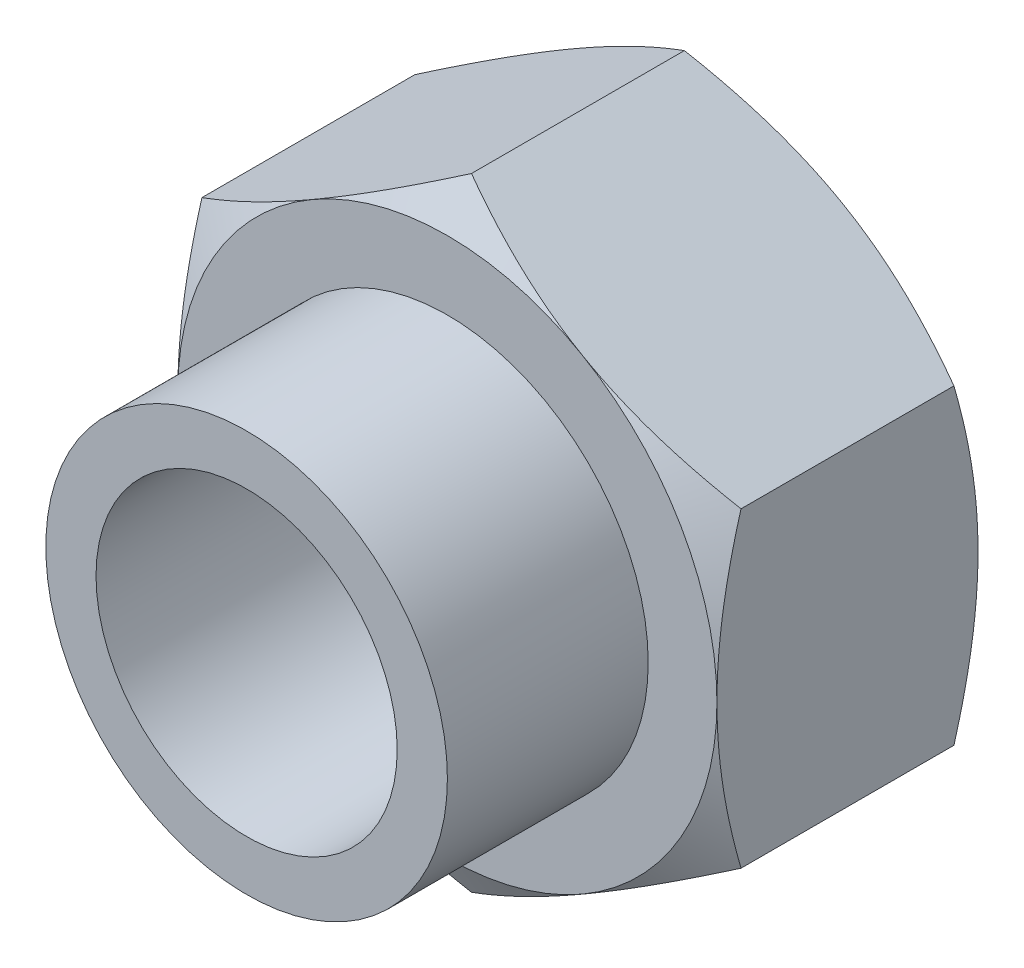
SolidWorks part; units mm, degrees
ref_plane "Front Plane" through (0, 0, 0) normal (0, 0, 1) x (1, 0, 0)
ref_plane "Top Plane" through (0, 0, 0) normal (0, 1, 0) x (1, 0, 0)
ref_plane "Right Plane" through (0, 0, 0) normal (1, 0, 0) x (0, 0, -1)
sketch "Sketch1" plane through (0, 0, 0) normal (0, 0, 1) x (1, 0, 0)
  line L1 (0, 77.5) -> (-67.117, 38.75)
  line L2 (-67.117, 38.75) -> (-67.117, -38.75)
  line L3 (-67.117, -38.75) -> (0, -77.5)
  line L4 (0, -77.5) -> (67.117, -38.75)
  line L5 (67.117, -38.75) -> (67.117, 38.75)
  line L6 (67.117, 38.75) -> (0, 77.5)
  circle A0 centre (0, 0) radius 67.117 construction
  circle A1 centre (0, 0) radius 37.5
  dimension "D2" = 75
  dimension "D1" = 155
extrude "Boss-Extrude1" add sketch "Sketch1" along normal mid plane 65
sketch "Sketch2" plane through (0, 0, 32.5) normal (0, 0, 1) x (1, 0, 0)
  circle A0 centre (0, 0) radius 67.117
extrude "Cut-Extrude1" cut sketch "Sketch2" against normal through all draft 60 flip side to cut
sketch "Sketch3" plane through (0, 0, -32.5) normal (0, 0, -1) x (-1, 0, 0)
  circle A0 centre (0, 0) radius 67.117
extrude "Cut-Extrude2" cut sketch "Sketch3" against normal through all draft 60 flip side to cut
sketch "Sketch4" plane through (0, 0, 32.5) normal (0, 0, 1) x (1, 0, 0)
  circle A0 centre (0, 0) radius 50
  circle A1 centre (0, 0) radius 37.5 construction
  circle A2 centre (0, 0) radius 37.5
  dimension "D1" = 100
extrude "Boss-Extrude2" add sketch "Sketch4" along normal blind 50
